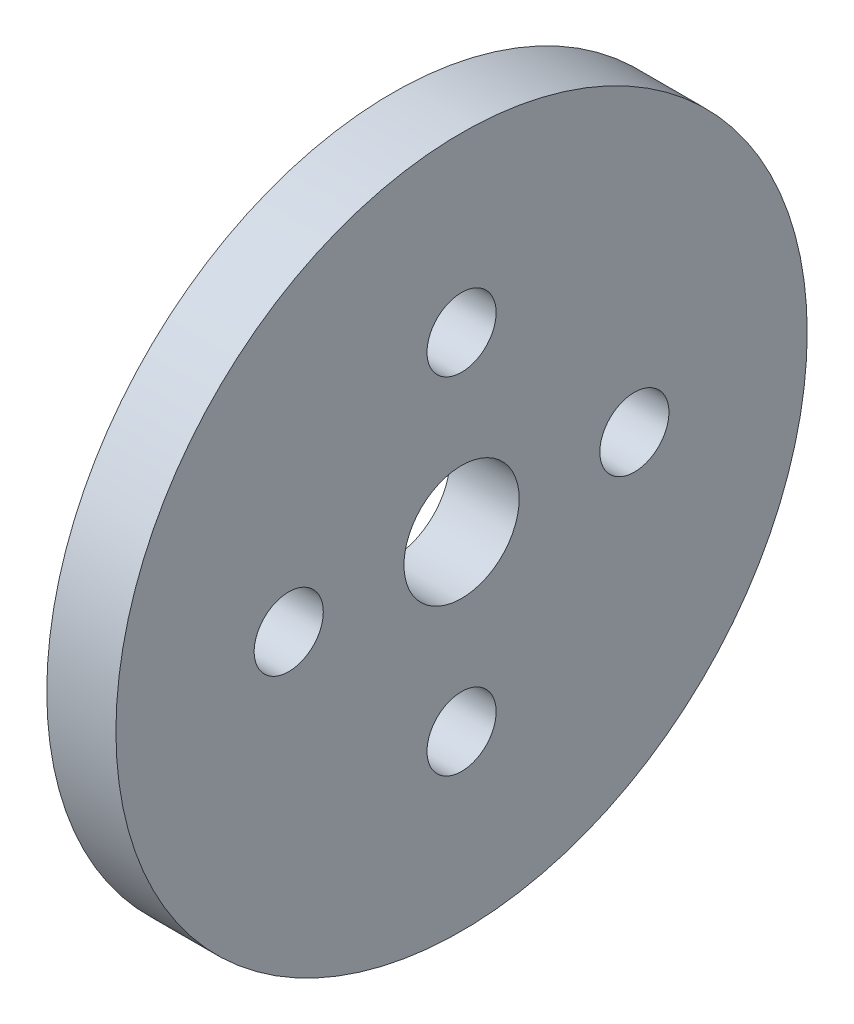
SolidWorks part; units mm, degrees
ref_plane "Alzado" through (0, 0, 0) normal (0, 0, 1) x (1, 0, 0)
ref_plane "Planta" through (0, 0, 0) normal (0, 1, 0) x (1, 0, 0)
ref_plane "Vista lateral" through (0, 0, 0) normal (1, 0, 0) x (0, 0, -1)
sketch "Croquis1" plane through (0, 0, 0) normal (1, 0, 0) x (0, 0, -1)
  line L0 (0, 0) -> (0, 7.5) construction
  circle A0 centre (0, 0) radius 15
  circle A1 centre (0, 0) radius 2.5
  circle A2 centre (0, 7.5) radius 1.5
  circle A3 centre (7.5, 0) radius 1.5
  circle A4 centre (0, -7.5) radius 1.5
  circle A5 centre (-7.5, 0) radius 1.5
  point P15 (0, 0)
  dimension "D1" = 4
extrude "Saliente-Extruir1" add sketch "Croquis1" along normal blind 3
